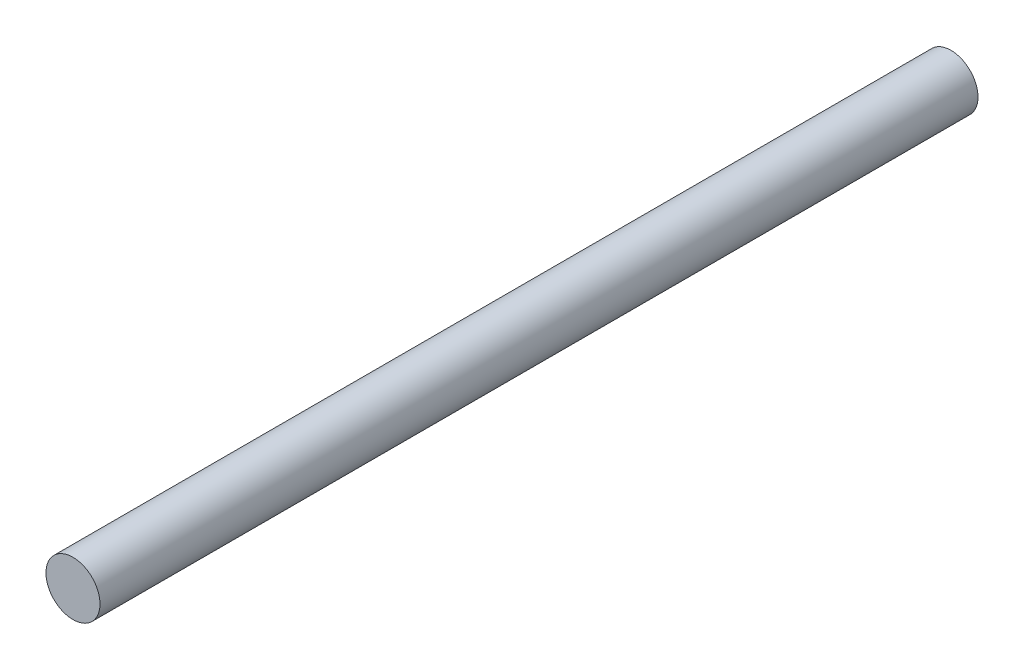
SolidWorks part; units mm, degrees
ref_plane "Plan de face" through (0, 0, 0) normal (0, 0, 1) x (1, 0, 0)
ref_plane "Plan de dessus" through (0, 0, 0) normal (0, 1, 0) x (1, 0, 0)
ref_plane "Plan de droite" through (0, 0, 0) normal (1, 0, 0) x (0, 0, -1)
sketch "Esquisse1" plane through (0, 0, 0) normal (0, 0, 1) x (1, 0, 0)
  circle A0 centre (0, 0) radius 4
  dimension "D1" = 8
extrude "Boss.-Extru.1" add sketch "Esquisse1" along normal blind 130
